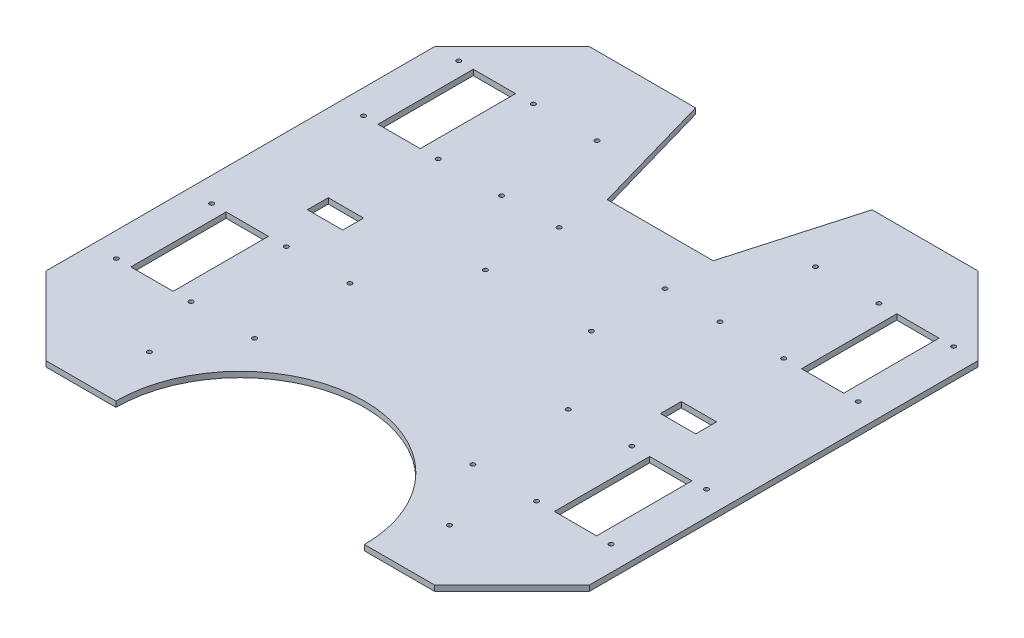
SolidWorks part; units mm, degrees
ref_plane "前视基准面" through (0, 0, 0) normal (0, 0, 1) x (1, 0, 0)
ref_plane "上视基准面" through (0, 0, 0) normal (0, 1, 0) x (1, 0, 0)
ref_plane "右视基准面" through (0, 0, 0) normal (1, 0, 0) x (0, 0, -1)
other "Configuration Table"
sketch "草图1" plane through (0, 0, 0) normal (0, 1, 0) x (1, 0, 0)
  line L0 (-184.763, 118.1289) -> (-154.363, 118.1289)
  line L1 (-141.489, 118.1289) -> (-95.769, 118.1289)
  line L2 (-95.769, 118.1289) -> (-95.769, 186.7089)
  line L3 (-154.363, 118.1289) -> (-141.489, 118.1289)
  line L4 (-195.203, 118.1289) -> (-184.763, 118.1289)
  line L5 (-184.763, 118.1289) -> (-154.363, 118.1289)
  line L6 (-184.763, 118.1289) -> (-154.363, 118.1289)
  line B0 (-154.363, -59.6711) -> (-154.363, 8.9089)
  line B1 (-154.363, 8.9089) -> (-184.763, 8.9089)
  line B2 (-184.763, 8.9089) -> (-184.763, -59.6711)
  line B3 (-184.763, -59.6711) -> (-154.363, -59.6711)
  line B4 (150.357, 118.1289) -> (150.357, 186.7089)
  line B5 (150.357, 186.7089) -> (119.957, 186.7089)
  line B6 (119.957, 186.7089) -> (119.957, 118.1289)
  line B7 (119.957, 118.1289) -> (150.357, 118.1289)
  line B8 (119.957, 8.9089) -> (119.957, -59.6711)
  line B9 (119.957, -59.6711) -> (150.357, -59.6711)
  line B10 (150.357, -59.6711) -> (150.357, 8.9089)
  line B11 (150.357, 8.9089) -> (119.957, 8.9089)
  line B12 (-154.363, 118.1289) -> (-154.363, 186.7089)
  line B13 (-154.363, 186.7089) -> (-184.763, 186.7089)
  line B14 (-184.763, 186.7089) -> (-184.763, 118.1289)
  line B15 (-184.763, 118.1289) -> (-154.363, 118.1289)
  line B16 (-131.503, 39.5089) -> (-131.503, 54.5089)
  line B17 (-131.503, 54.5089) -> (-156.903, 54.5089)
  line B18 (-156.903, 54.5089) -> (-156.903, 39.5089)
  line B19 (-156.903, 39.5089) -> (-131.503, 39.5089)
  line B20 (122.497, 39.5089) -> (122.497, 54.5089)
  line B21 (122.497, 54.5089) -> (97.097, 54.5089)
  line B22 (97.097, 54.5089) -> (97.097, 39.5089)
  line B23 (97.097, 39.5089) -> (122.497, 39.5089)
  line B24 (-212.783, -92.6911) -> (-212.783, 186.7089)
  line B25 (-156.903, 242.5889) -> (-212.783, 186.7089)
  line B26 (-80.703, 242.5889) -> (-156.903, 242.5889)
  line B27 (-80.703, 242.5889) -> (-55.303, 153.6889)
  line B28 (-55.303, 153.6889) -> (20.897, 153.6889)
  line B29 (46.297, 242.5889) -> (20.897, 153.6889)
  line B30 (122.497, 242.5889) -> (46.297, 242.5889)
  line B31 (122.497, 242.5889) -> (178.377, 186.7089)
  line B32 (178.377, -92.6911) -> (178.377, 186.7089)
  line B33 (178.377, -92.6911) -> (122.497, -148.5711)
  line B34 (122.497, -148.5711) -> (72.205, -148.5711)
  line B35 (-106.611, -148.5711) -> (-156.903, -148.5711)
  line B36 (-156.903, -148.5711) -> (-212.783, -92.6911)
  circle B37 centre (-141.489, 186.7089) radius 1.55
  circle B38 centre (20.897, 66.0089) radius 1.55
  circle B39 centre (90.747, -105.9911) radius 1.55
  circle B40 centre (-125.153, -105.9911) radius 1.55
  circle B41 centre (-141.489, 118.1289) radius 1.55
  circle B42 centre (-95.769, 118.1289) radius 1.55
  circle B43 centre (107.083, 118.1289) radius 1.55
  circle B44 centre (-141.489, 8.9089) radius 1.55
  circle B45 centre (61.363, 118.1289) radius 1.55
  circle B46 centre (61.363, 186.7089) radius 1.55
  circle B47 centre (-141.489, -59.6711) radius 1.55
  circle B48 centre (-95.769, -59.6711) radius 1.55
  circle B49 centre (-95.769, 186.7089) radius 1.55
  circle B50 centre (107.083, -59.6711) radius 1.55
  circle B51 centre (61.363, -59.6711) radius 1.55
  circle B52 centre (107.083, 186.7089) radius 1.55
  circle B53 centre (160.797, 186.7089) radius 1.55
  circle B54 centre (-195.203, 118.1289) radius 1.55
  circle B55 centre (-195.203, 186.7089) radius 1.55
  circle B56 centre (160.797, 8.9089) radius 1.55
  circle B57 centre (-55.303, 66.0089) radius 1.55
  circle B58 centre (20.897, 119.0089) radius 1.55
  circle B59 centre (-55.303, 119.0089) radius 1.55
  circle B60 centre (160.797, 118.1289) radius 1.55
  circle B61 centre (107.083, 8.9089) radius 1.55
  circle B62 centre (61.363, 8.9089) radius 1.55
  circle B63 centre (-95.769, 8.9089) radius 1.55
  circle B64 centre (-195.203, 8.9089) radius 1.55
  circle B65 centre (-195.203, -59.6711) radius 1.55
  circle B66 centre (160.797, -59.6711) radius 1.55
  arc B67 (72.205, -148.5711) -> (-106.611, -148.5711) centre (-17.203, -148.5711) ccw
  dimension "D1" = 10.44
  dimension "D2" = 12.874
  dimension "D3" = 45.72
  dimension "D4" = 68.58
  dimension "D5" = 30.4
sketch_block_instance "chassis-1"
sketch_block "chassis"
extrude "凸台-拉伸1" add sketch "草图1" along normal blind 4
